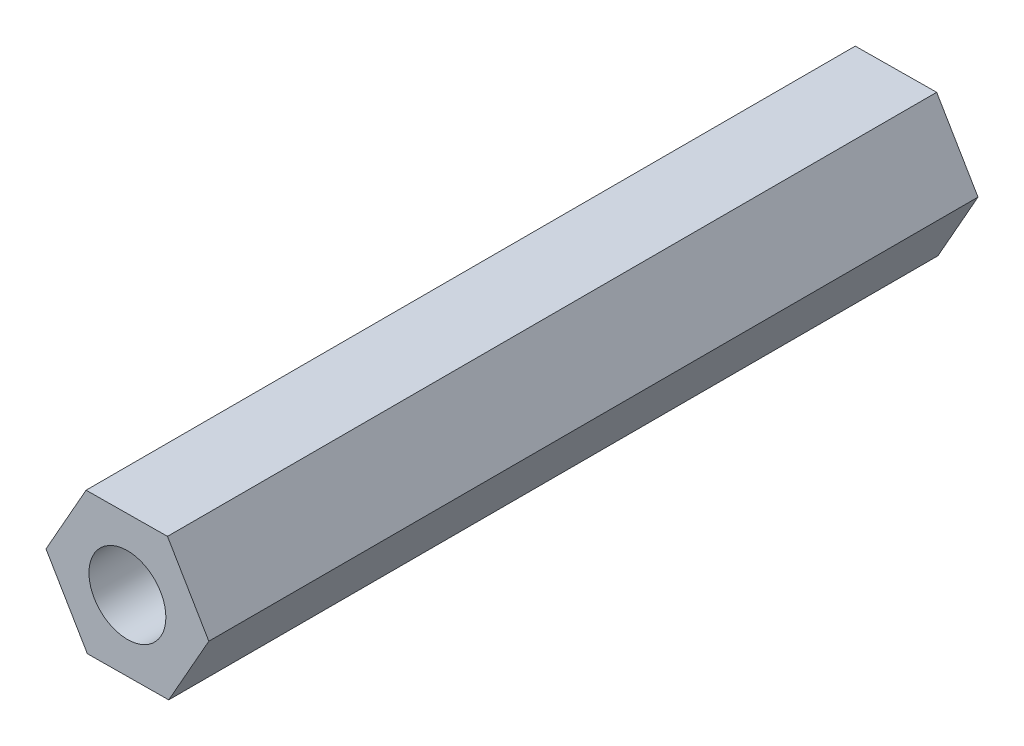
SolidWorks part; units mm, degrees
ref_plane "前视基准面" through (0, 0, 0) normal (0, 0, 1) x (1, 0, 0)
ref_plane "上视基准面" through (0, 0, 0) normal (0, 1, 0) x (1, 0, 0)
ref_plane "右视基准面" through (0, 0, 0) normal (1, 0, 0) x (0, 0, -1)
sketch "草图1" plane through (0, 0, 0) normal (0, 0, 1) x (1, 0, 0)
  line L1 (1.6119, -2.7359) -> (3.1753, 0.028)
  line L2 (3.1753, 0.028) -> (1.5634, 2.7639)
  line L3 (1.5634, 2.7639) -> (-1.6119, 2.7359)
  line L4 (-1.6119, 2.7359) -> (-3.1753, -0.028)
  line L5 (-3.1753, -0.028) -> (-1.5634, -2.7639)
  line L6 (-1.5634, -2.7639) -> (1.6119, -2.7359)
  circle A0 centre (0, 0) radius 2.75 construction
  circle A1 centre (0, 0) radius 1.5
extrude "凸台-拉伸1" add sketch "草图1" along normal blind 30
